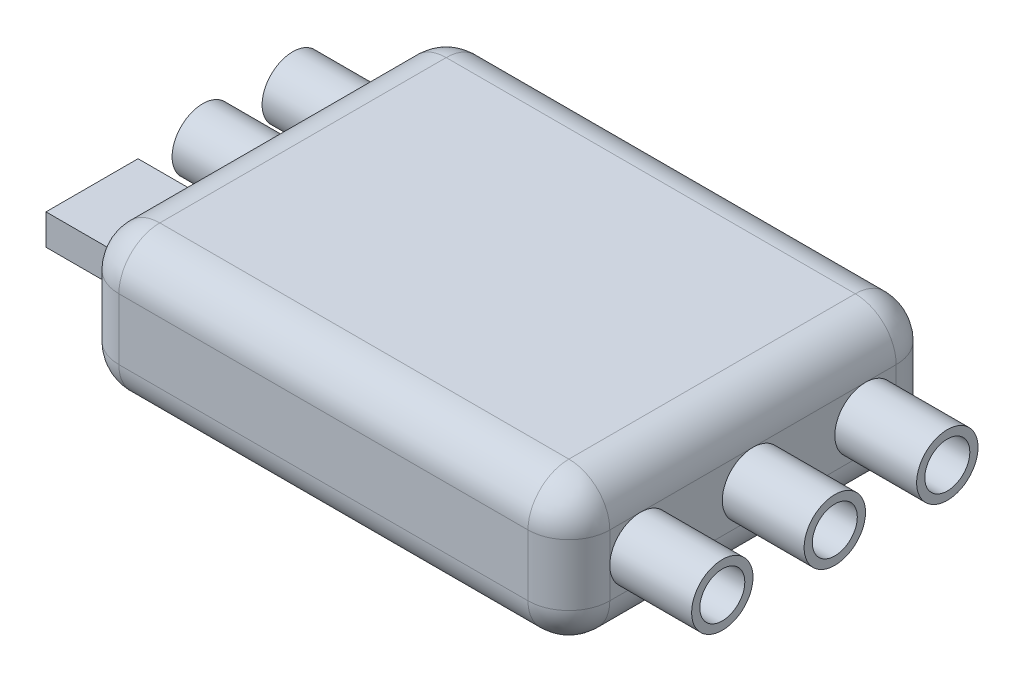
SolidWorks part; units mm, degrees
ref_plane "Front Plane" through (0, 0, 0) normal (0, 0, 1) x (1, 0, 0)
ref_plane "Top Plane" through (0, 0, 0) normal (0, 1, 0) x (1, 0, 0)
ref_plane "Right Plane" through (0, 0, 0) normal (1, 0, 0) x (0, 0, -1)
sketch "Sketch1" plane through (0, 0, 0) normal (0, 1, 0) x (1, 0, 0)
  line L1 (10, -9) -> (-10, -9)
  line L2 (12, -7) -> (12, 7)
  line L3 (10, 9) -> (-10, 9)
  line L4 (-12, -7) -> (-12, 7)
  line L5 (12, -9) -> (-12, 9) construction
  line L6 (12, 9) -> (-12, -9) construction
  arc A0 (-10, -9) -> (-12, -7) centre (-10, -7) cw
  arc A1 (12, 7) -> (10, 9) centre (10, 7) ccw
  arc A2 (10, -9) -> (12, -7) centre (10, -7) ccw
  arc A3 (-10, 9) -> (-12, 7) centre (-10, 7) ccw
  point P0 (0, 0)
  dimension "D3" = 2
  dimension "D1" = 24
  dimension "D2" = 18
extrude "Boss-Extrude1" add sketch "Sketch1" along normal blind 7
fillet "Fillet1" radius 2 16 edges at (0, 0, 9) (11.4142, 0, 8.4142) (12, 0, 0) (11.4142, 0, -8.4142) (0, 0, -9) (-11.4142, 0, -8.4142) (-12, 0, 0) (-11.4142, 0, 8.4142) (-12, 7, 0) (-11.4142, 7, -8.4142) (0, 7, -9) (11.4142, 7, -8.4142) (12, 7, 0) (11.4142, 7, 8.4142) (0, 7, 9) (-11.4142, 7, 8.4142)
sketch "Sketch2" plane through (12, 0, 0) normal (1, 0, 0) x (0, 0, -1)
  line L0 (-7, 3.5) -> (7, 3.5) construction
  line L1 (-7, 5) -> (-7, 2) construction
  line L2 (7, 5) -> (7, 2) construction
  circle A0 centre (0, 3.5) radius 1.5
  circle A1 centre (0, 3.5) radius 1.1
  circle A2 centre (-5.5, 3.5) radius 1.5
  circle A3 centre (-5.5, 3.5) radius 1.1
  circle A4 centre (5.5, 3.5) radius 1.5
  circle A5 centre (5.5, 3.5) radius 1.1
  dimension "D1" = 3
  dimension "D2" = 0.4
extrude "Boss-Extrude2" add sketch "Sketch2" along normal blind 4
sketch "Sketch3" plane through (-12, 0, 0) normal (-1, 0, 0) x (0, 0, 1)
  line L0 (-7, 3.5) -> (7, 3.5) construction
  line L1 (-7, 5) -> (-7, 2) construction
  line L2 (7, 5) -> (7, 2) construction
  line L4 (6.5634, 4.25) -> (2.0634, 4.25)
  line L5 (6.5634, 4.25) -> (6.5634, 2.75)
  line L6 (6.5634, 2.75) -> (2.0634, 2.75)
  line L7 (2.0634, 4.25) -> (2.0634, 2.75)
  circle A0 centre (-5.5, 3.5) radius 1.5
  circle A1 centre (-5.5, 3.5) radius 1.1
  circle A2 centre (-1.1, 3.5) radius 1.5
  circle A3 centre (-1.1, 3.5) radius 1.1
  point P17 (1.719, 4.25)
  point P18 (6.5634, 4.25)
  dimension "D3" = 3
  dimension "D4" = 0.4
  dimension "D1" = 4.5
  dimension "D2" = 1.5
  dimension "D5" = 4.4
extrude "Boss-Extrude4" add sketch "Sketch3" along normal blind 4
